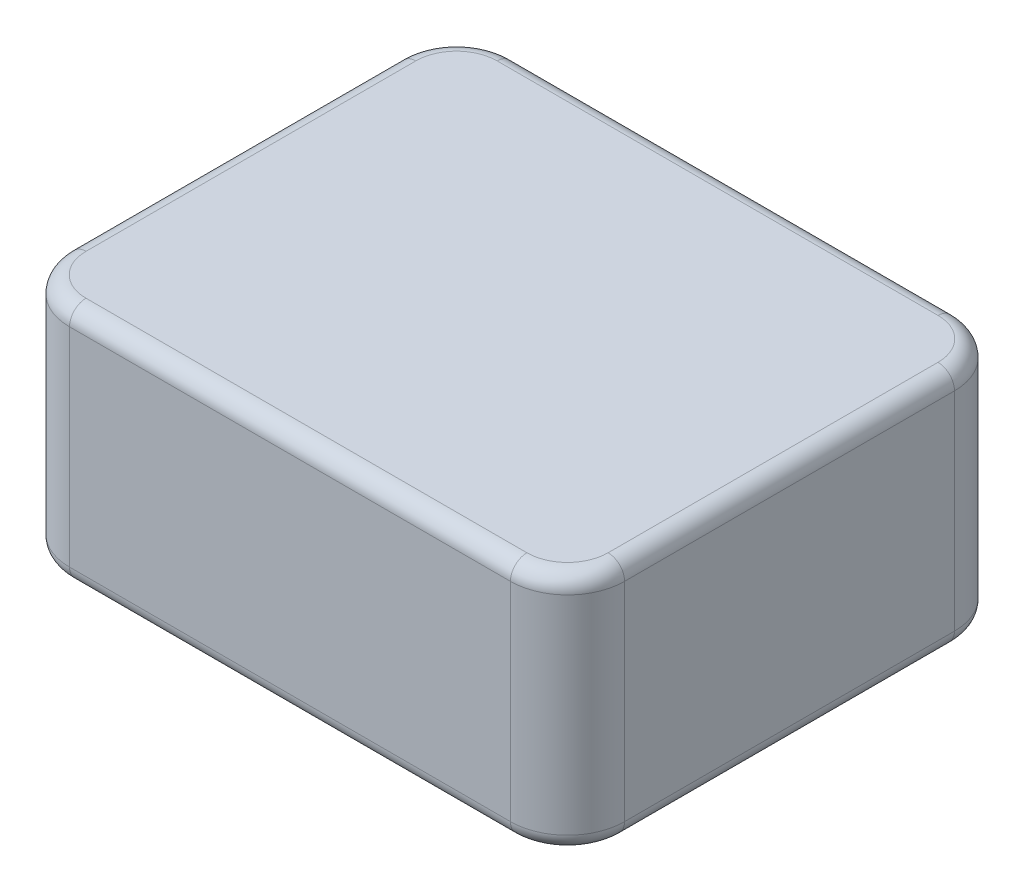
SolidWorks part; units mm, degrees
ref_plane "Front Plane" through (0, 0, 0) normal (0, 0, 1) x (1, 0, 0)
ref_plane "Top Plane" through (0, 0, 0) normal (0, 1, 0) x (1, 0, 0)
ref_plane "Right Plane" through (0, 0, 0) normal (1, 0, 0) x (0, 0, -1)
sketch "Sketch2" plane through (0, 0, 0) normal (0, 1, 0) x (1, 0, 0)
  line L1 (11.43, 0) -> (99.695, 0)
  line L2 (0, 11.43) -> (0, 77.47)
  line L3 (11.43, 88.9) -> (99.695, 88.9)
  line L4 (111.125, 11.43) -> (111.125, 77.47)
  arc A0 (0, 77.47) -> (11.43, 88.9) centre (11.43, 77.47) cw
  arc A1 (99.695, 88.9) -> (111.125, 77.47) centre (99.695, 77.47) cw
  arc A2 (99.695, 0) -> (111.125, 11.43) centre (99.695, 11.43) ccw
  arc A3 (11.43, 0) -> (0, 11.43) centre (11.43, 11.43) cw
  point P13 (0, 0)
  dimension "D3" = 11.43
  dimension "D1" = 111.125
  dimension "D2" = 88.9
extrude "Extrude1" add sketch "Sketch2" along normal blind 48.26
fillet "Fillet1" radius 3.302 16 edges at (55.5625, 48.26, -88.9) (107.7772, 48.26, -85.5522) (111.125, 48.26, -44.45) (107.7772, 48.26, -3.3478) (55.5625, 48.26, 0) (3.3478, 48.26, -3.3478) (0, 48.26, -44.45) (3.3478, 48.26, -85.5522) (0, 0, -44.45) (3.3478, 0, -3.3478) (55.5625, 0, 0) (107.7772, 0, -3.3478) (111.125, 0, -44.45) (107.7772, 0, -85.5522) (55.5625, 0, -88.9) (3.3478, 0, -85.5522)
